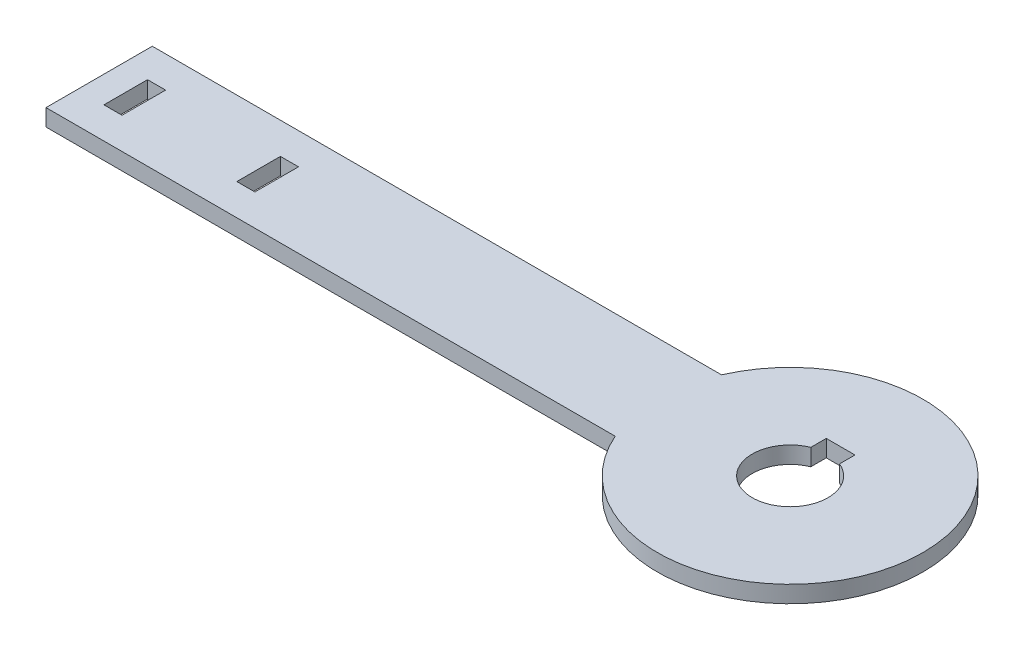
SolidWorks part; units mm, degrees
ref_plane "Front Plane" through (0, 0, 0) normal (0, 0, 1) x (1, 0, 0)
ref_plane "Top Plane" through (0, 0, 0) normal (0, 1, 0) x (1, 0, 0)
ref_plane "Right Plane" through (0, 0, 0) normal (1, 0, 0) x (0, 0, -1)
sketch "Sketch1" plane through (0, 0, 0) normal (0, 1, 0) x (1, 0, 0)
  line L0 (-22.9129, 0) -> (-125, 0) construction
  line L7 (-22.9129, -10) -> (-125, -10)
  line L8 (-22.9129, 10) -> (-125, 10)
  line L9 (-22.9129, 0) -> (0, 0) construction
  line L14 (-22.9129, 10) -> (-22.9129, -10) construction
  line L15 (-125, 10) -> (-125, -10) construction
  line L17 (-2.7, 6.5936) -> (-2.7, 9.5)
  line L18 (-2.7, 9.5) -> (2.7, 9.5)
  line L19 (2.7, 9.5) -> (2.7, 6.5936)
  line L20 (0, 0) -> (0, 9.5) construction
  line L21 (0, 32.5) -> (0, 0) construction
  line L22 (0, 0) -> (32.5, 0) construction
  line L23 (-125, 4.1) -> (-125, -4.1)
  line L24 (0, -32.5) -> (0, 0) construction
  line L28 (-125, 10) -> (-130, 10)
  line L29 (-130, 10) -> (-130, -10)
  line L30 (-130, -10) -> (-125, -10)
  line L31 (-125, 4.1) -> (-121.6, 4.1)
  line L32 (-121.6, 4.1) -> (-121.6, -4.1)
  line L33 (-121.6, -4.1) -> (-125, -4.1)
  line L34 (-100, 4.1) -> (-100, -4.1)
  line L35 (-100, -4.1) -> (-96.6, -4.1)
  line L36 (-96.6, -4.1) -> (-96.6, 4.1)
  line L37 (-96.6, 4.1) -> (-100, 4.1)
  arc A0 (-2.7, 6.5936) -> (2.7, 6.5936) centre (0, 0) ccw
  circle A1 centre (0, 0) radius 32.5 construction
  circle A10 centre (-85, 0) radius 1.5 construction
  circle A12 centre (0, 0) radius 25
  dimension "D1" = 14.25
  dimension "D2" = 65
  dimension "D5" = 5
  dimension "D11" = 9.5
  dimension "D15" = 3
  dimension "D3" = 50
  dimension "D4" = 130
  dimension "D6" = 8.2
  dimension "D7" = 20
  dimension "D8" = 15
  dimension "D10" = 5.4
  dimension "D14" = 3.4
  dimension "D16" = 25
extrude "Boss-Extrude1" add sketch "Sketch1" along normal blind 3.175
